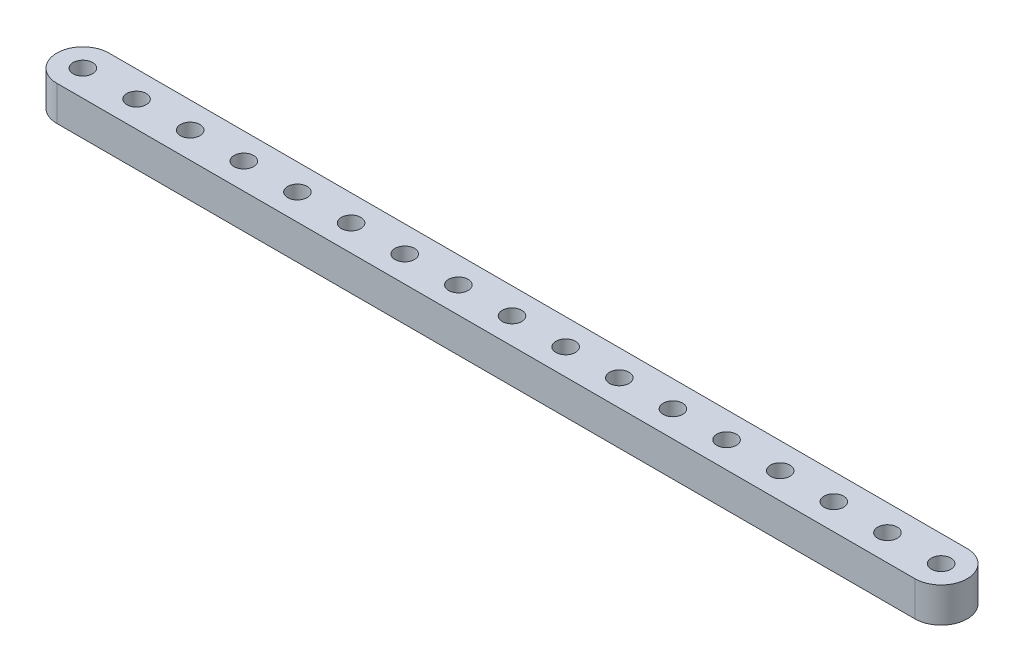
SolidWorks part; units mm, degrees
ref_plane "Front Plane" through (0, 0, 0) normal (0, 0, 1) x (1, 0, 0)
ref_plane "Top Plane" through (0, 0, 0) normal (0, 1, 0) x (1, 0, 0)
ref_plane "Right Plane" through (0, 0, 0) normal (1, 0, 0) x (0, 0, -1)
ref_plane "Plane1" through (0, 6.35, 0) normal (0, 1, 0) x (1, 0, 0)
sketch "Sketch1" plane through (0, 6.35, 0) normal (0, 1, 0) x (1, 0, 0)
  line L0 (78.232, 4.7625) -> (-78.232, 4.7625)
  line L1 (-78.232, -4.7625) -> (78.232, -4.7625)
  arc A0 (78.232, -4.7625) -> (78.232, 4.7625) centre (78.232, 0) ccw
  arc A1 (-78.232, 4.7625) -> (-78.232, -4.7625) centre (-78.232, 0) ccw
  circle A2 centre (78.232, 0) radius 1.778
  circle A3 centre (68.453, 0) radius 1.778
  circle A4 centre (58.674, 0) radius 1.778
  circle A5 centre (48.895, 0) radius 1.778
  circle A6 centre (39.116, 0) radius 1.778
  circle A7 centre (29.337, 0) radius 1.778
  circle A8 centre (19.558, 0) radius 1.778
  circle A9 centre (9.779, 0) radius 1.778
  circle A10 centre (0, 0) radius 1.778
  circle A11 centre (-9.779, 0) radius 1.778
  circle A12 centre (-19.558, 0) radius 1.778
  circle A13 centre (-29.337, 0) radius 1.778
  circle A14 centre (-39.116, 0) radius 1.778
  circle A15 centre (-48.895, 0) radius 1.778
  circle A16 centre (-58.674, 0) radius 1.778
  circle A17 centre (-68.453, 0) radius 1.778
  circle A18 centre (-78.232, 0) radius 1.778
extrude "Boss-Extrude1" add sketch "Sketch1" against normal blind 6.35
sketch "Sketch2" plane through (0, 6.35, 0) normal (0, 1, 0) x (1, 0, 0)
  line L0 (-78.232, -4.7625) -> (78.232, -4.7625) construction
  line L1 (-83.0214, 4.8036) -> (-63.5635, 4.8036)
  line L2 (-83.0214, 4.8036) -> (-83.0214, -4.7625)
  line L3 (-83.0214, -4.7625) -> (-63.5635, -4.7625)
  line L4 (-63.5635, 4.8036) -> (-63.5635, -4.7625)
  circle A0 centre (-68.453, 0) radius 1.778 construction
  dimension "D1" = 4.8895
